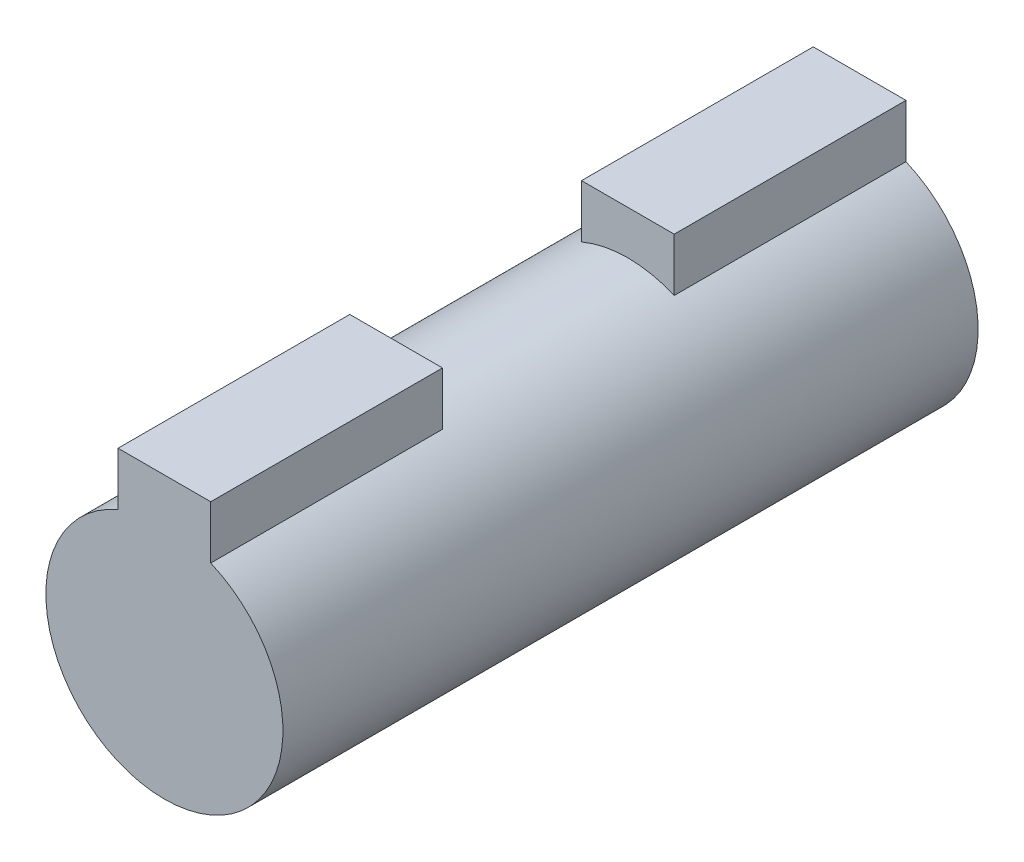
SolidWorks part; units mm, degrees
ref_plane "Front Plane" through (0, 0, 0) normal (0, 0, 1) x (1, 0, 0)
ref_plane "Top Plane" through (0, 0, 0) normal (0, 1, 0) x (1, 0, 0)
ref_plane "Right Plane" through (0, 0, 0) normal (1, 0, 0) x (0, 0, -1)
sketch "Sketch1" plane through (0, 0, 0) normal (0, 0, 1) x (1, 0, 0)
  line L0 (0, 0) -> (0, 5.7198) construction
  line L3 (-2, 4.7078) -> (-2, 7)
  line L4 (-2, 7) -> (2, 7)
  line L5 (2, 4.7078) -> (2, 7)
  arc A0 (-2, 4.7078) -> (2, 4.7078) centre (0, 0) ccw
  dimension "D1" = 10.23
  dimension "D2" = 4
  dimension "D3" = 7
extrude "Boss-Extrude1" add sketch "Sketch1" along normal blind 30
sketch "Sketch2" plane through (0, 0, 30) normal (0, 0, 1) x (1, 0, 0)
  circle A0 centre (0, 0) radius 5.115
  circle A1 centre (0, 0) radius 7.8225
extrude "Cut-Extrude1" cut sketch "Sketch2" against normal blind 10 from offset 10
